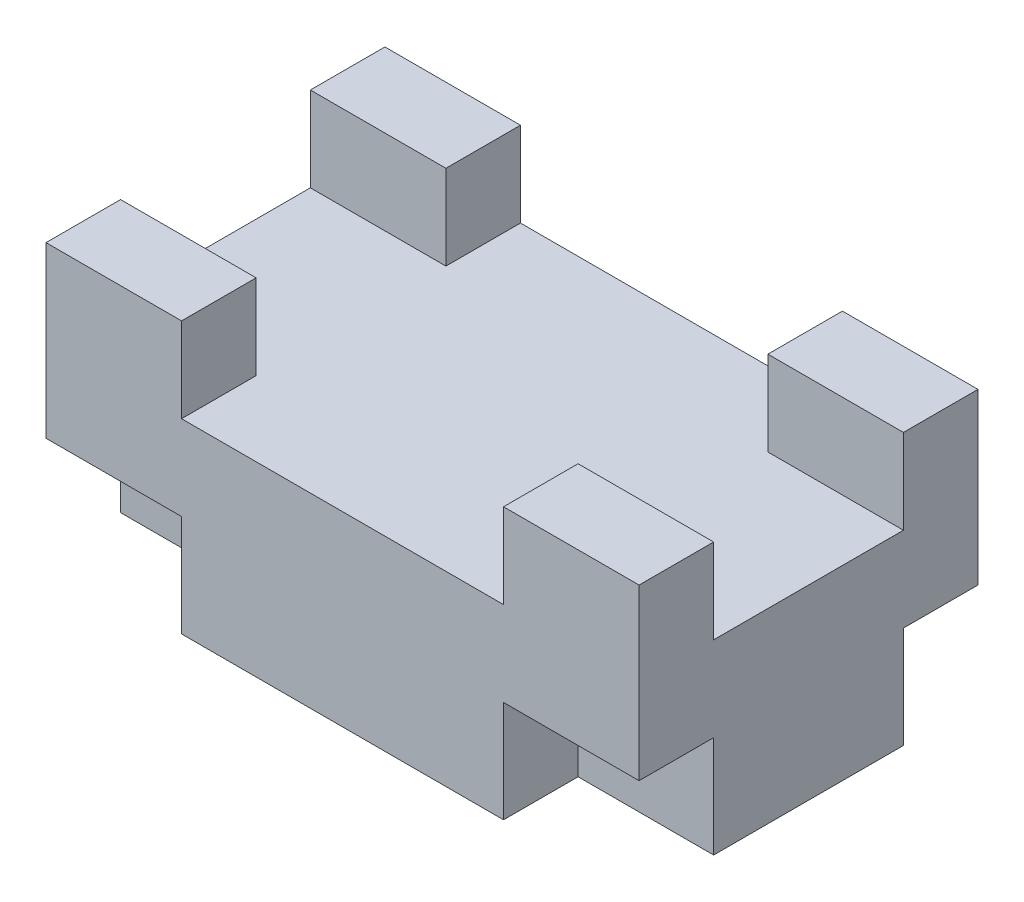
SolidWorks part; units mm, degrees
ref_plane "Płaszczyzna przednia" through (0, 0, 0) normal (0, 0, 1) x (1, 0, 0)
ref_plane "Płaszczyzna górna" through (0, 0, 0) normal (0, 1, 0) x (1, 0, 0)
ref_plane "Płaszczyzna prawa" through (0, 0, 0) normal (1, 0, 0) x (0, 0, -1)
sketch "Szkic2" plane through (0, 0, 0) normal (0, 1, 0) x (1, 0, 0)
  line L1 (-87.5, 50) -> (87.5, 50)
  line L2 (-87.5, 50) -> (-87.5, -50)
  line L3 (-87.5, -50) -> (87.5, -50)
  line L4 (87.5, 50) -> (87.5, -50)
  line L5 (-87.5, 50) -> (87.5, -50) construction
  line L6 (-87.5, -50) -> (87.5, 50) construction
  point P0 (0, 0)
  dimension "D1" = 100
  dimension "D2" = 175
extrude "Dodanie-wyciągnięcie1" add sketch "Szkic2" along normal blind 55
sketch "Szkic3" plane through (0, 55, 0) normal (0, 1, 0) x (1, 0, 0)
  line L0 (0, 0) -> (0, 50) construction
  line L1 (47.5, 50) -> (87.5, 50)
  line L2 (47.5, 50) -> (47.5, 28)
  line L3 (47.5, 28) -> (87.5, 28)
  line L4 (87.5, 50) -> (87.5, 28)
  line L5 (87.5, 50) -> (-87.5, 50) construction
  line L6 (0, 0) -> (87.5, 0) construction
  line L7 (87.5, -50) -> (87.5, 50) construction
  line L8 (-47.5, 28) -> (-87.5, 28)
  line L9 (-87.5, 50) -> (-87.5, 28)
  line L10 (-47.5, 50) -> (-87.5, 50)
  line L11 (-47.5, 50) -> (-47.5, 28)
  line L12 (47.5, -28) -> (87.5, -28)
  line L13 (87.5, -50) -> (87.5, -28)
  line L14 (47.5, -50) -> (87.5, -50)
  line L15 (47.5, -50) -> (47.5, -28)
  line L16 (-47.5, -50) -> (-47.5, -28)
  line L17 (-47.5, -50) -> (-87.5, -50)
  line L18 (-87.5, -50) -> (-87.5, -28)
  line L19 (-47.5, -28) -> (-87.5, -28)
  dimension "D1" = 40
  dimension "D2" = 22
extrude "Dodanie-wyciągnięcie2" add sketch "Szkic3" along normal blind 25
sketch "Szkic4" plane through (0, 0, 0) normal (0, -1, 0) x (1, 0, 0)
  line L0 (0, 0) -> (0, 50) construction
  line L1 (-87.5, 50) -> (-47.5, 50)
  line L2 (-87.5, 50) -> (-87.5, 28)
  line L3 (-87.5, 28) -> (-47.5, 28)
  line L4 (-47.5, 50) -> (-47.5, 28)
  line L5 (-87.5, 50) -> (87.5, 50) construction
  line L6 (0, 0) -> (87.5, 0) construction
  line L7 (87.5, 50) -> (87.5, -50) construction
  line L8 (87.5, 28) -> (47.5, 28)
  line L9 (47.5, 50) -> (47.5, 28)
  line L10 (87.5, 50) -> (47.5, 50)
  line L11 (87.5, 50) -> (87.5, 28)
  line L12 (87.5, -50) -> (87.5, -28)
  line L13 (87.5, -50) -> (47.5, -50)
  line L14 (47.5, -50) -> (47.5, -28)
  line L15 (87.5, -28) -> (47.5, -28)
  line L16 (-87.5, -28) -> (-47.5, -28)
  line L17 (-47.5, -50) -> (-47.5, -28)
  line L18 (-87.5, -50) -> (-47.5, -50)
  line L19 (-87.5, -50) -> (-87.5, -28)
  dimension "D1" = 40
  dimension "D2" = 22
extrude "Wytnij-wyciągnięcie1" cut sketch "Szkic4" against normal blind 30
